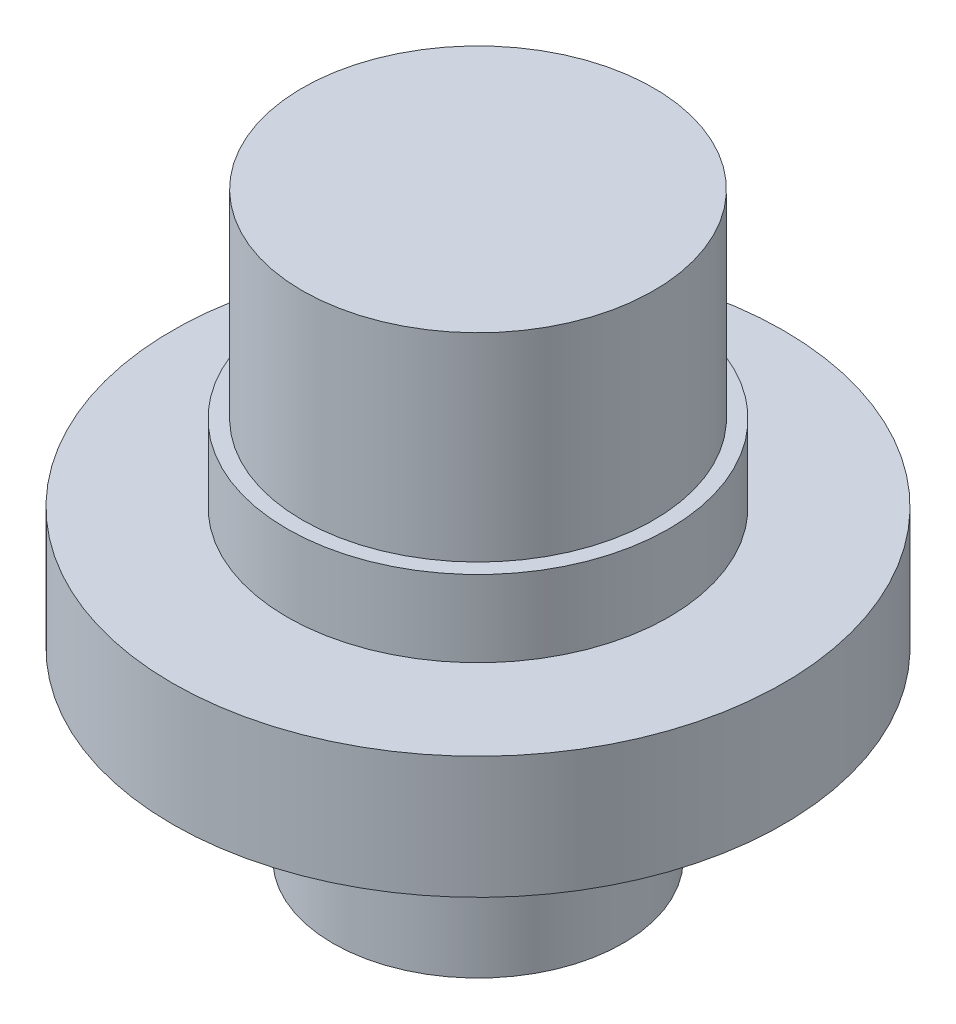
SolidWorks part; units mm, degrees
ref_plane "Front Plane" through (0, 0, 0) normal (0, 0, 1) x (1, 0, 0)
ref_plane "Top Plane" through (0, 0, 0) normal (0, 1, 0) x (1, 0, 0)
ref_plane "Right Plane" through (0, 0, 0) normal (1, 0, 0) x (0, 0, -1)
sketch "Sketch2" plane through (0, 0, 0) normal (0, 1, 0) x (1, 0, 0)
  circle A0 centre (0, 0) radius 9.5
  dimension "D1" = 19
extrude "Boss-Extrude1" add sketch "Sketch2" along normal blind 12
sketch "Sketch3" plane through (0, 12, 0) normal (0, 1, 0) x (1, 0, 0)
  circle A0 centre (0, 0) radius 20
  dimension "D1" = 40
extrude "Boss-Extrude2" add sketch "Sketch3" along normal blind 8
sketch "Sketch4" plane through (0, 20, 0) normal (0, 1, 0) x (1, 0, 0)
  circle A0 centre (0, 0) radius 12.5
  dimension "D1" = 25
extrude "Boss-Extrude3" add sketch "Sketch4" along normal blind 5
sketch "Sketch5" plane through (0, 25, 0) normal (0, 1, 0) x (1, 0, 0)
  circle A0 centre (0, 0) radius 11.5
  dimension "D1" = 23
extrude "Boss-Extrude4" add sketch "Sketch5" along normal blind 13
